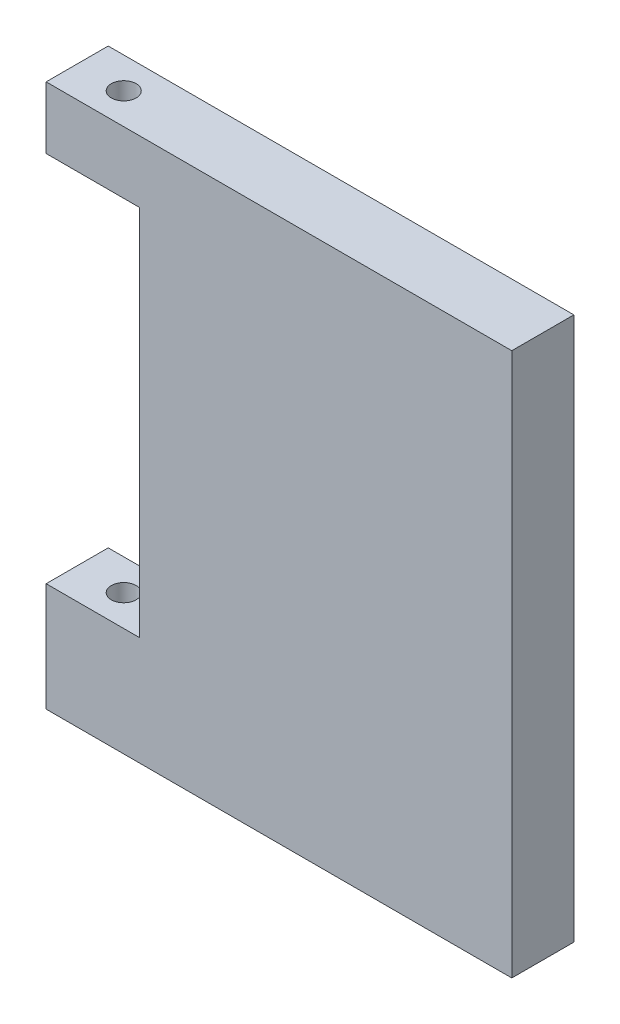
SolidWorks part; units mm, degrees
material "Клен"
ref_plane "Спереди" through (0, 0, 0) normal (0, 0, 1) x (1, 0, 0)
ref_plane "Сверху" through (0, 0, 0) normal (0, 1, 0) x (1, 0, 0)
ref_plane "Справа" through (0, 0, 0) normal (1, 0, 0) x (0, 0, -1)
sketch "Эскиз1" plane through (0, 0, 0) normal (0, 0, 1) x (1, 0, 0)
  line L0 (-300, 310) -> (-300, 350)
  line L1 (0, 0) -> (-300, 0)
  line L2 (0, 0) -> (0, 350)
  line L3 (0, 350) -> (-300, 350)
  line L4 (-300, 0) -> (-300, 70)
  line L5 (-300, 310) -> (-240, 310)
  line L7 (-300, 70) -> (-240, 70)
  line L8 (-240, 310) -> (-240, 70)
  dimension "D1" = 300
  dimension "D2" = 350
  dimension "D3" = 60
  dimension "D4" = 70
  dimension "D5" = 40
extrude "Бобышка-Вытянуть1" add sketch "Эскиз1" along normal blind 40
sketch "Эскиз2" plane through (0, 350, 0) normal (0, 1, 0) x (1, 0, 0)
  line L0 (-270, 0) -> (-270, -40) construction
  line L1 (0, 0) -> (-300, 0) construction
  line L2 (0, -40) -> (-300, -40) construction
  line L3 (-300, -40) -> (-300, 0) construction
  circle A0 centre (-270, -20) radius 8
  dimension "D2" = 16
  dimension "D1" = 30
extrude "Вырез-Вытянуть1" cut sketch "Эскиз2" against normal blind 300
sketch "Эскиз3" plane through (0, 0, 0) normal (0, -1, 0) x (1, 0, 0)
  line L0 (0, 20) -> (-300, 20) construction
  line L1 (0, 40) -> (0, 0) construction
  line L2 (-300, 40) -> (-300, 0) construction
  circle A0 centre (-30, 20) radius 4
  circle A1 centre (-120, 20) radius 4
  circle A2 centre (-210, 20) radius 4
  dimension "D1" = 8
  dimension "D2" = 8
  dimension "D3" = 8
  dimension "D4" = 30
  dimension "D5" = 120
  dimension "D6" = 210
extrude "Вырез-Вытянуть2" cut sketch "Эскиз3" against normal blind 50
